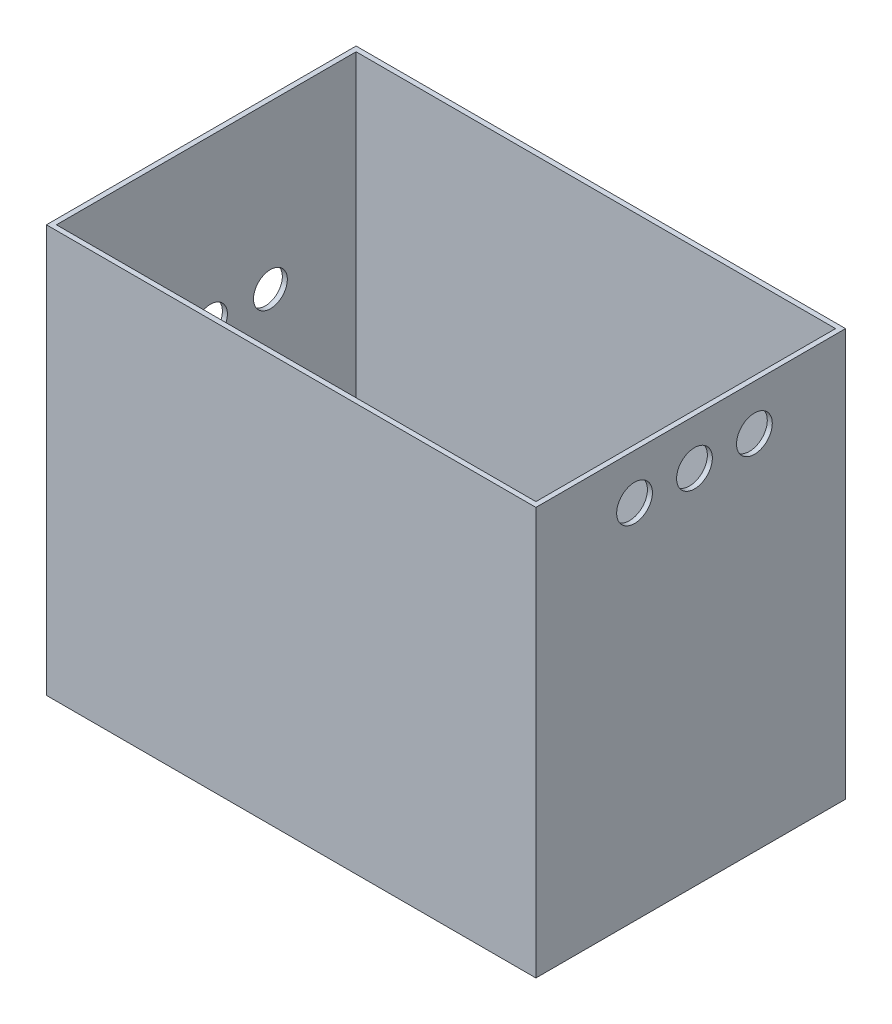
SolidWorks part; units mm, degrees
ref_plane "Front Plane" through (0, 0, 0) normal (0, 0, 1) x (1, 0, 0)
ref_plane "Top Plane" through (0, 0, 0) normal (0, 1, 0) x (1, 0, 0)
ref_plane "Right Plane" through (0, 0, 0) normal (1, 0, 0) x (0, 0, -1)
sketch "Sketch1" plane through (0, 0, 0) normal (0, 1, 0) x (1, 0, 0)
  line L1 (-152.4, -95.25) -> (0, -95.25)
  line L2 (-152.4, -95.25) -> (-152.4, 95.25)
  line L3 (-152.4, 95.25) -> (0, 95.25)
  line L4 (0, -95.25) -> (0, 95.25)
  point P0 (0, 0)
  dimension "D1" = 190.5
  dimension "D2" = 152.4
extrude "Boss-Extrude1" add sketch "Sketch1" along normal blind 5.08 contours L2 L1 L4 L3
sketch "Sketch2" plane through (0, 5.08, 0) normal (0, 1, 0) x (1, 0, 0)
  line L1 (155.575, -98.425) -> (-155.575, -98.425)
  line L2 (155.575, -98.425) -> (155.575, 98.425)
  line L3 (155.575, 98.425) -> (-155.575, 98.425)
  line L4 (-155.575, -98.425) -> (-155.575, 98.425)
  line L5 (155.575, -98.425) -> (-155.575, 98.425) construction
  line L6 (155.575, 98.425) -> (-155.575, -98.425) construction
  point P0 (0, 0)
  dimension "D1" = 196.85
  dimension "D2" = 311.15
extrude "Boss-Extrude2" add sketch "Sketch2" along normal blind 254 and the other way blind 5.08
sketch "Sketch3" plane through (0, 259.08, 0) normal (0, 1, 0) x (1, 0, 0)
  line L1 (152.4, -95.25) -> (-152.4, -95.25)
  line L2 (152.4, -95.25) -> (152.4, 95.25)
  line L3 (152.4, 95.25) -> (-152.4, 95.25)
  line L4 (-152.4, -95.25) -> (-152.4, 95.25)
  line L5 (152.4, -95.25) -> (-152.4, 95.25) construction
  line L6 (152.4, 95.25) -> (-152.4, -95.25) construction
  point P0 (0, 0)
  dimension "D1" = 190.5
  dimension "D2" = 304.8
extrude "Cut-Extrude1" cut sketch "Sketch3" against normal blind 252.73
sketch "Sketch4" plane through (-155.575, 0, 0) normal (-1, 0, 0) x (0, 0, 1)
  circle A0 centre (-40.7826, 155.6311) radius 10.7594
  circle A1 centre (-2.6826, 155.6311) radius 10.7594
  circle A2 centre (35.4174, 155.6311) radius 10.7594
  dimension "D1" = 3
extrude "Cut-Extrude2" cut sketch "Sketch4" against normal blind 252.73
sketch "Sketch5" plane through (155.575, 0, 0) normal (1, 0, 0) x (0, 0, -1)
  circle A0 centre (-35.725, 230.2102) radius 11.3686
  circle A1 centre (2.375, 230.2102) radius 11.3686
  circle A2 centre (40.475, 230.2102) radius 11.3686
  dimension "D1" = 3
extrude "Cut-Extrude3" cut sketch "Sketch5" against normal blind 252.73
